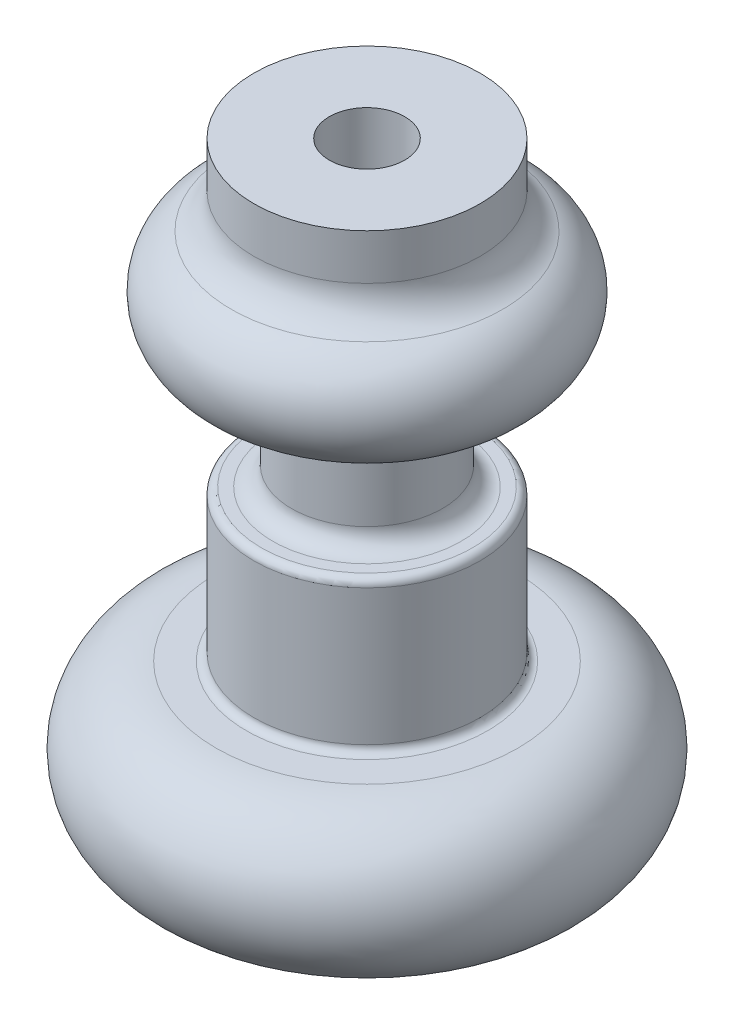
SolidWorks part; units mm, degrees
ref_plane "Front Plane" through (0, 0, 0) normal (0, 0, 1) x (1, 0, 0)
ref_plane "Top Plane" through (0, 0, 0) normal (0, 1, 0) x (1, 0, 0)
ref_plane "Right Plane" through (0, 0, 0) normal (1, 0, 0) x (0, 0, -1)
sketch "Sketch1" plane through (0, 0, 0) normal (0, 0, 1) x (1, 0, 0)
  line L0 (0, 0) -> (47252.5307, 0) construction
  line L1 (0, 0) -> (0, 47252.5307) construction
  line L2 (0, -95.2142) -> (40, -95.2142)
  line L3 (40, -55.2142) -> (32, -55.2142)
  line L4 (30, -53.2142) -> (30, -17.2142)
  line L5 (28, -15.2142) -> (25, -15.2142)
  line L6 (20, -10.2142) -> (20, 4.7858)
  line L7 (0, -95.2142) -> (0, 24.7858)
  line L8 (30, 52.6986) -> (30, 64.7858)
  line L9 (30, 64.7858) -> (10, 64.7858)
  line L10 (10, 64.7858) -> (10, 24.7858)
  line L11 (10, 24.7858) -> (0, 24.7858)
  arc A0 (40, -95.2142) -> (40, -55.2142) centre (40, -75.2142) ccw
  arc A1 (30, 14.7858) -> (36, 43.5335) centre (30, 29.7858) ccw
  arc A2 (36, 43.5335) -> (30, 52.6986) centre (40, 52.6986) cw
  arc A3 (25, -15.2142) -> (20, -10.2142) centre (25, -10.2142) cw
  arc A4 (32, -55.2142) -> (30, -53.2142) centre (32, -53.2142) cw
  arc A5 (30, -17.2142) -> (28, -15.2142) centre (28, -17.2142) ccw
  arc A6 (20, 4.7858) -> (30, 14.7858) centre (30, 4.7858) cw
  point P26 (30, -55.2142)
  point P30 (0, 0)
  point P31 (0, 0)
  point P32 (0, 0)
  point P33 (0, 0)
  dimension "D2" = 20
  dimension "D8" = 15
  dimension "D11" = 10
  dimension "D12" = 5
  dimension "D13" = 2
  dimension "D16" = 10
  dimension "D1" = 80
  dimension "D3" = 20
  dimension "D4" = 40
  dimension "D5" = 60
  dimension "D6" = 125
  dimension "D7" = 160
  dimension "D9" = 60
  dimension "D10" = 40
  dimension "D14" = 100
  dimension "D15" = 85
revolve "Revolve1" add sketch "Sketch1" angle 360 about L1
